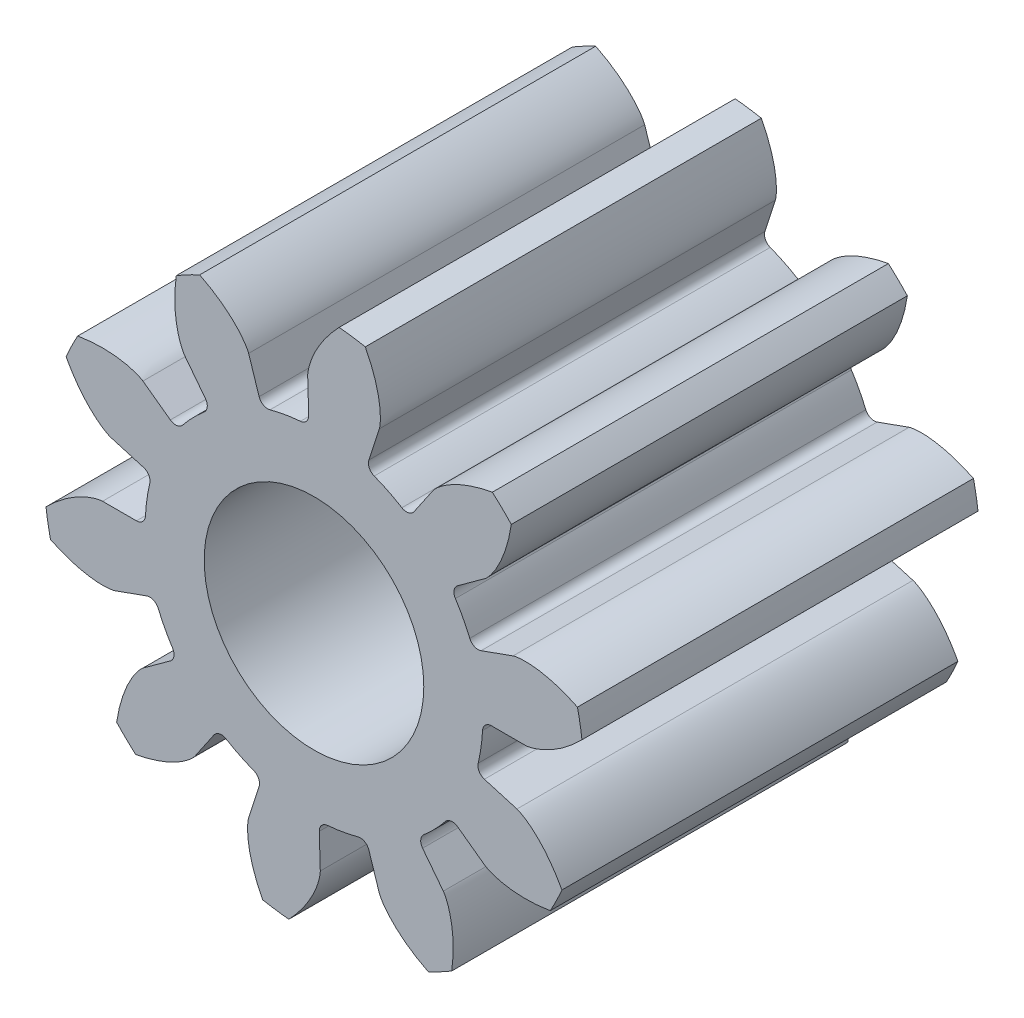
SolidWorks part; units mm, degrees
material "AISI 1020"
ref_plane "Front Plane" through (0, 0, 0) normal (0, 0, 1) x (1, 0, 0)
ref_plane "Top Plane" through (0, 0, 0) normal (0, 1, 0) x (1, 0, 0)
ref_plane "Right Plane" through (0, 0, 0) normal (1, 0, 0) x (0, 0, -1)
sketch "Sketch3" plane through (0, 0, 0) normal (0, 0, 1) x (1, 0, 0)
  circle A0 centre (0, 0) radius 3
  dimension "D1" = 6
extrude "Boss-Extrude1" add sketch "Sketch3" along normal blind 4.4 contours A0
sketch "Sketch4" plane through (0, 0, 0) normal (0, 0, 1) x (1, 0, 0)
  line L0 (2.3492, 0) -> (1.875, 0)
  line L1 (0, 0) -> (2.9697, -0.4251) construction
  line L2 (2.2549, -0.659) -> (1.7997, -0.526)
  circle A0 centre (0, 0) radius 2.5 construction
  circle A1 centre (0, 0) radius 2.3492 construction
  arc A2 (1.7997, -0.526) -> (1.875, 0) centre (0, 0) ccw
  circle A3 centre (0, 0) radius 3 construction
  spline S0 degree 4 poles (2.3492, 0) (2.3532, 0.0001) (2.3606, 0.0007) (2.3727, 0.0021) (2.3965, 0.006) (2.4232, 0.0122) (2.4529, 0.0207) (2.4846, 0.0314) (2.5113, 0.0416) (2.5378, 0.0526) (2.5639, 0.0644) (2.5952, 0.0796) (2.6322, 0.0991) (2.6748, 0.1238) (2.7221, 0.1539) (2.7692, 0.1869) (2.8146, 0.2212) (2.8594, 0.2579) (2.9019, 0.2949) (2.9447, 0.3354) (2.9836, 0.3737) (3.0256, 0.4189) (3.0591, 0.4559) (3.1016, 0.5071) (3.1262, 0.5379) (3.1544, 0.5748) (3.1666, 0.5916) (3.1741, 0.6019) knots 0 0 0 0 0 0.015084 0.028532 0.04661 0.092111 0.119476 0.146842 0.174209 0.201575 0.228941 0.256307 0.307035 0.361767 0.4165 0.471232 0.525964 0.580697 0.635429 0.690161 0.744894 0.799626 0.854358 0.909091 0.954545 1 1 1 1 1 construction
  spline S1 degree 4 poles (2.3492, 0) (2.3532, 0.0001) (2.3606, 0.0007) (2.3727, 0.0021) (2.3965, 0.006) (2.4232, 0.0122) (2.4529, 0.0207) (2.4846, 0.0314) (2.5113, 0.0416) (2.5378, 0.0526) (2.5639, 0.0644) (2.5952, 0.0796) (2.6322, 0.0991) (2.6748, 0.1238) (2.7221, 0.1539) (2.7692, 0.1869) (2.8146, 0.2212) (2.8594, 0.2579) (2.9019, 0.2949) (2.9447, 0.3354) (2.9836, 0.3737) (3.0256, 0.4189) (3.0591, 0.4559) (3.0924, 0.496) (3.1084, 0.5157) (3.1165, 0.5259) knots 0 0 0 0 0 0.015084 0.028532 0.04661 0.092111 0.119476 0.146842 0.174209 0.201575 0.228941 0.256307 0.307035 0.361767 0.4165 0.471232 0.525964 0.580697 0.635429 0.690161 0.744894 0.799626 0.854358 0.909091 0.909091 0.909091 0.909091 0.909091
  spline S2 degree 4 poles (106.284, -15.4902) (106.3203, -15.496) (106.4217, -15.5139) (106.6124, -15.5542) (106.9218, -15.6289) (107.4928, -15.787) (108.3484, -16.0665) (109.2774, -16.4238) (110.2481, -16.846) (111.0925, -17.2464) (111.7606, -17.5817) (112.5627, -18.0056) (113.5166, -18.5412) (114.6147, -19.2012) (115.8472, -19.9983) (117.0769, -20.8493) (118.2809, -21.7356) (119.4604, -22.6553) (120.4702, -23.4858) (121.322, -24.2171) (122.1596, -24.9594) (122.8519, -25.5935) (123.5262, -26.2293) (124.2037, -26.8891) (124.7206, -27.4019) (125.2693, -27.9609) (125.7445, -28.4521) (126.1894, -28.925) (126.4234, -29.1763) (126.5387, -29.301) knots 0 0 0 0 0 0.005377 0.015084 0.028532 0.04661 0.092111 0.146842 0.174209 0.201575 0.228941 0.256307 0.307035 0.361767 0.4165 0.471232 0.525964 0.580697 0.635429 0.662795 0.690161 0.744894 0.77226 0.799626 0.826992 0.854358 0.881725 0.909091 0.909091 0.909091 0.909091 0.909091
  spline S3 degree 4 poles (2.2549, -0.659) (2.2587, -0.6602) (2.2657, -0.6629) (2.2769, -0.6676) (2.2986, -0.6781) (2.3224, -0.6915) (2.3486, -0.708) (2.376, -0.7272) (2.3988, -0.7444) (2.4211, -0.7624) (2.4429, -0.781) (2.4686, -0.8044) (2.4987, -0.8335) (2.5326, -0.8692) (2.5696, -0.9114) (2.6056, -0.9563) (2.6396, -1.0019) (2.6722, -1.0497) (2.7026, -1.0971) (2.7324, -1.148) (2.7589, -1.1957) (2.7866, -1.2508) (2.8084, -1.2958) (2.8291, -1.3436) (2.8389, -1.367) (2.8438, -1.3791) knots 0 0 0 0 0 0.015084 0.028532 0.04661 0.092111 0.119476 0.146842 0.174209 0.201575 0.228941 0.256307 0.307035 0.361767 0.4165 0.471232 0.525964 0.580697 0.635429 0.690161 0.744894 0.799626 0.854358 0.909091 0.909091 0.909091 0.909091 0.909091
  dimension "D1" = 5
  dimension "D2" = 4.6985
  dimension "D3" = 3.75
sketch "Sketch5" plane through (0, 0, 0) normal (0, 0, -1) x (-1, 0, 0)
sketch "Sketch6" plane through (0, 0, 4.4) normal (0, 0, 1) x (1, 0, 0)
  spline S0 degree 4 poles (2.2181, -0.6446) (2.222, -0.6458) (2.2305, -0.6487) (2.2487, -0.6561) (2.2615, -0.6619) (2.2873, -0.6749) (2.3071, -0.6864) (2.3335, -0.7025) (2.3584, -0.7198) (2.3846, -0.7391) (2.4091, -0.7588) (2.4336, -0.7795) (2.457, -0.8009) (2.4853, -0.828) (2.5181, -0.8619) (2.5548, -0.9028) (2.5947, -0.952) (2.6325, -1.0026) (2.6688, -1.0561) (2.7021, -1.1086) (2.7349, -1.166) (2.7635, -1.2184) (2.7939, -1.2818) (2.8162, -1.3295) (2.8455, -1.4013) (2.8592, -1.437) (2.8765, -1.4851) (2.8836, -1.5063) (2.8875, -1.5181) knots 0 0 0 0 0 0.016103 0.035225 0.053961 0.072698 0.099517 0.127623 0.155728 0.183834 0.21194 0.240045 0.268151 0.296257 0.35018 0.406391 0.462602 0.518814 0.575025 0.631236 0.687448 0.743659 0.79987 0.856082 0.912293 0.956147 1 1 1 1 1 construction
  spline S1 degree 4 poles (2.2549, -0.659) (2.2591, -0.661) (2.2674, -0.6649) (2.2873, -0.6749) (2.3071, -0.6864) (2.3335, -0.7025) (2.3584, -0.7198) (2.3846, -0.7391) (2.4091, -0.7588) (2.4336, -0.7795) (2.457, -0.8009) (2.4853, -0.828) (2.5181, -0.8619) (2.5548, -0.9028) (2.5947, -0.952) (2.6325, -1.0026) (2.6688, -1.0561) (2.7021, -1.1086) (2.7349, -1.166) (2.7635, -1.2184) (2.7939, -1.2818) (2.8162, -1.3295) (2.8394, -1.3865) (2.8493, -1.4116) (2.8543, -1.4246) knots 0.035225 0.035225 0.035225 0.035225 0.035225 0.053961 0.072698 0.099517 0.127623 0.155728 0.183834 0.21194 0.240045 0.268151 0.296257 0.35018 0.406391 0.462602 0.518814 0.575025 0.631236 0.687448 0.743659 0.79987 0.856082 0.912293 0.912293 0.912293 0.912293 0.912293
sketch "Sketch7" plane through (0, 0, 0) normal (0, 0, -1) x (-1, 0, 0)
sketch "Sketch8" plane through (0, 0, 4.4) normal (0, 0, 1) x (1, 0, 0)
  circle A0 centre (0, 0) radius 1.215
extrude "Cut-Extrude3" cut sketch "Sketch4" against normal through all and the other way through all contours S1 L0 A2 L2 S3
pattern_circular "CirPattern2" count 10 over 360 about axis through (0, 0, 4.4) along (0, 0, 1) of "Cut-Extrude3"
sketch "Sketch9" plane through (0, 0, 4.4) normal (0, 0, 1) x (1, 0, 0)
  circle A0 centre (0, 0) radius 1.22
extrude "Cut-Extrude4" cut sketch "Sketch9" against normal through all
fillet "Fillet2" radius 0.1 20 edges at (1.1468, -1.4834, 2.2) (1.5169, -1.1021, 2.2) (0.0559, -1.8742, 2.2) (0.5794, -1.7832, 2.2) (-1.0564, -1.5491, 2.2) (-0.5794, -1.7832, 2.2) (-1.5169, -1.1021, 2.2) (-1.1468, 1.4834, 2.2) (-1.5169, 1.1021, 2.2) (-0.0559, 1.8742, 2.2) (-0.5794, 1.7832, 2.2) (1.0564, 1.5491, 2.2) (0.5794, 1.7832, 2.2) (1.7652, 0.6323, 2.2) (1.5169, 1.1021, 2.2) (1.7997, -0.526, 2.2) (1.875, 0, 2.2) (-1.7652, -0.6323, 2.2) (-1.875, 0, 2.2) (-1.7997, 0.526, 2.2)
sketch "Sketch10" plane through (0, 0, 0) normal (0, 0, -1) x (-1, 0, 0)
  circle A0 centre (0, 0) radius 2.5
equation "\"P\"= 2'Diametral Pitch"
equation "\"N\"= 10'Numver of teeth"
equation "\"phi\"= 20deg'Pressure Angle"
equation "\"a\"= 1 / \"P\"'Addendum"
equation "\"b\"= 1.25 / \"P\"'Dedendun"
equation "\"c\"= \"b\" - \"a\"'clearance"
equation "\"dp\"= \"N\" / \"P\"'pitch circle diameter"
equation "\"db\"= \"dp\" * cos ( \"phi\" )'base circle diameter"
equation "\"D1@Sketch3\"= \"dp\" + 2 * \"a\""
equation "\"D1@Sketch4\"= \"dp\"'Pitch circle diametr"
equation "\"D2@Sketch4\"= \"db\"'Base Circle"
equation "\"D3@Sketch4\"= \"dp\" - 2 * \"b\""
equation "\"alpha\"= sqr ( \"dp\" ^ 2 - \"db\" ^ 2 ) / \"db\" * 180 / pi - \"phi\""
equation "\"Beta\"= ( 360 / ( 4 * \"N\" ) - \"alpha\" ) * 2"
